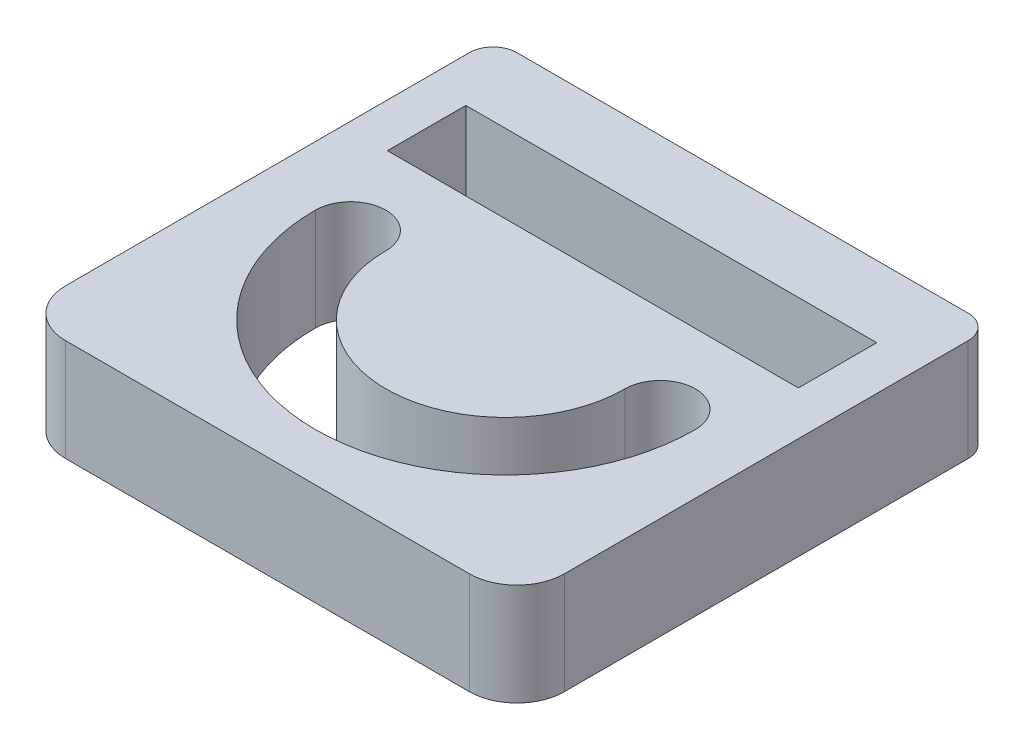
SolidWorks part; units mm, degrees
ref_plane "Plano frontal" through (0, 0, 0) normal (0, 0, 1) x (1, 0, 0)
ref_plane "Plano superior" through (0, 0, 0) normal (0, 1, 0) x (1, 0, 0)
ref_plane "Plano direito" through (0, 0, 0) normal (1, 0, 0) x (0, 0, -1)
sketch "Esboço2" plane through (0, 0, 0) normal (0, 1, 0) x (1, 0, 0)
  line L1 (-10.5, -10) -> (10.5, -10)
  line L2 (-10.5, -10) -> (-10.5, 10)
  line L3 (-10.5, 10) -> (10.5, 10)
  line L4 (10.5, -10) -> (10.5, 10)
  line L5 (-10.5, -10) -> (10.5, 10) construction
  line L6 (-10.5, 10) -> (10.5, -10) construction
  line L7 (-8.65, 7) -> (8.65, 7)
  line L8 (-8.65, 7) -> (-8.65, 3.7)
  line L9 (-8.65, 3.7) -> (8.65, 3.7)
  line L10 (8.65, 7) -> (8.65, 3.7)
  line L11 (-8.65, 7) -> (8.65, 3.7) construction
  line L12 (-8.65, 3.7) -> (8.65, 7) construction
  point P0 (0, 0)
  point P6 (0, 5.35)
  dimension "D1" = 17.3
  dimension "D2" = 3.3
  dimension "D3" = 21
  dimension "D4" = 3
  dimension "D5" = 20
extrude "Ressalto-extrusão1" add sketch "Esboço2" along normal blind 4.3
fillet "Filete1" radius 1 1 edges at (10.5, 2.15, -10)
fillet "Filete2" radius 1 1 edges at (-10.5, 2.15, -10)
fillet "Filete3" radius 2 1 edges at (-10.5, 2.15, 10)
fillet "Filete4" radius 2 1 edges at (10.5, 2.15, 10)
sketch "Esboço6" plane through (0, 4.3, 0) normal (0, 1, 0) x (1, 0, 0)
  arc A0 (6.5163, 0.0163) -> (-6.5163, 0.0163) centre (0, 0.0163) cw construction
  arc A1 (-8, 0.0163) -> (8, 0.0163) centre (0, 0.0163) ccw
  arc A2 (-5.0325, 0.0163) -> (5.0325, 0.0163) centre (0, 0.0163) ccw
  arc A3 (-5.0325, 0.0163) -> (-8, 0.0163) centre (-6.5163, 0.0163) ccw
  arc A4 (8, 0.0163) -> (5.0325, 0.0163) centre (6.5163, 0.0163) ccw
  point P3 (0, -6.5)
  dimension "D2" = 8
  dimension "D1" = 6.5
extrude "Corte-extrusão3" cut sketch "Esboço6" against normal blind 4.3
